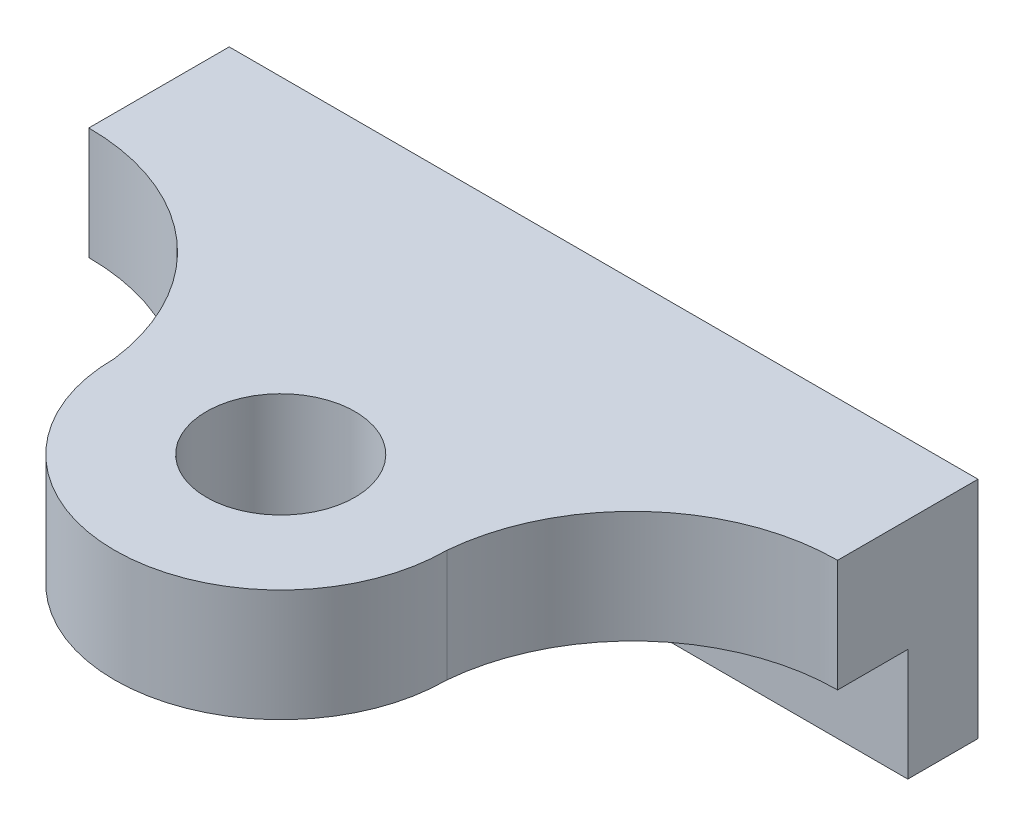
SolidWorks part; units mm, degrees
ref_plane "Front Plane" through (0, 0, 0) normal (0, 0, 1) x (1, 0, 0)
ref_plane "Top Plane" through (0, 0, 0) normal (0, 1, 0) x (1, 0, 0)
ref_plane "Right Plane" through (0, 0, 0) normal (1, 0, 0) x (0, 0, -1)
sketch "Sketch1" plane through (0, 0, 0) normal (0, 1, 0) x (1, 0, 0)
  circle A0 centre (0, 0) radius 17.75
  circle A1 centre (0, 0) radius 7.94
  point P0 (0, 0)
  dimension "D2" = 35.5
  dimension "D1" = 15.88
extrude "Boss-Extrude1" add sketch "Sketch1" along normal blind 12
sketch "Sketch6" plane through (0, 0, 0) normal (0, -1, 0) x (1, 0, 0)
  line L0 (-0.4563, -19.9527) -> (-40.4563, -19.9527)
  line L1 (-0.4563, -19.9527) -> (39.5437, -19.9527)
  arc A0 (-40.4563, -19.9527) -> (-17.75, 0) centre (-40.4563, 2.9437) ccw
  arc A1 (39.5437, -19.9527) -> (17.75, 0) centre (39.5437, 1.9259) cw
  arc A4 (-17.75, 0) -> (17.75, 0) centre (0, 0) ccw
  point P19 (0, 0)
  dimension "D1" = 40
  dimension "D2" = 40
extrude "Boss-Extrude6" add sketch "Sketch6" against normal blind 12
sketch "Sketch9" plane through (0, 0, 0) normal (0, -1, 0) x (-1, 0, 0)
  line L0 (40.4563, 19.9527) -> (-39.5437, 19.9527)
  line L1 (40.4563, 19.9527) -> (40.4563, 34.9527)
  line L2 (-39.5437, 19.9527) -> (-39.5437, 34.9527)
  line L3 (40.4563, 34.9527) -> (-39.5437, 34.9527)
  line L4 (40.4563, 19.9527) -> (-39.5437, 19.9527) construction
  dimension "D1" = 15
extrude "Boss-Extrude7" add sketch "Sketch9" against normal blind 12
sketch "Sketch10" plane through (0, 0, 0) normal (0, -1, 0) x (1, 0, 0)
  line L1 (39.5437, -34.9527) -> (-40.4563, -34.9527)
  line L2 (39.5437, -34.9527) -> (39.5437, -27.4527)
  line L3 (39.5437, -27.4527) -> (-40.4563, -27.4527)
  line L4 (-40.4563, -34.9527) -> (-40.4563, -27.4527)
  line L5 (-40.4563, -19.9527) -> (-40.4563, -34.9527) construction
  dimension "D1" = 7.5
  dimension "D2" = 80
extrude "Boss-Extrude8" add sketch "Sketch10" along normal blind 12
